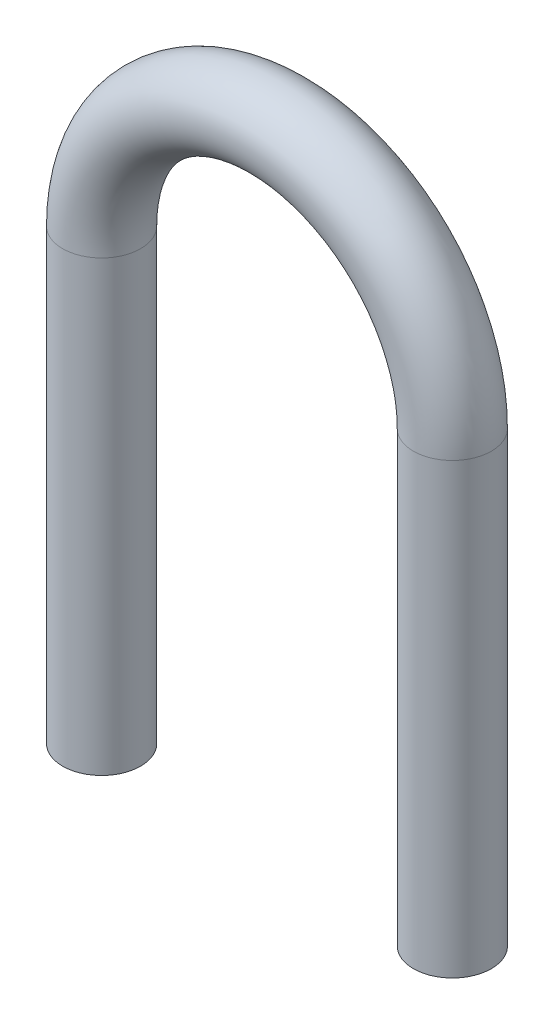
SolidWorks part; units mm, degrees
material "Stainless Steel (ferritic)"
ref_plane "Front Plane" through (0, 0, 0) normal (0, 0, 1) x (1, 0, 0)
ref_plane "Top Plane" through (0, 0, 0) normal (0, 1, 0) x (1, 0, 0)
ref_plane "Right Plane" through (0, 0, 0) normal (1, 0, 0) x (0, 0, -1)
sketch "Sketch1" plane through (0, 0, 0) normal (0, 0, 1) x (1, 0, 0)
  line L0 (-13.5, -13.5) -> (-13.5, -48)
  line L1 (13.5, -13.5) -> (13.5, -48)
  arc A0 (13.5, -13.5) -> (-13.5, -13.5) centre (0, -13.5) ccw
  point P3 (0, 0)
  dimension "D1" = 13.5
  dimension "D2" = 48
ref_plane "Plane1" through (0, -48, 0) normal (0, 1, 0) x (1, 0, 0)
sketch "Sketch2" plane through (0, -48, 0) normal (0, 1, 0) x (1, 0, 0)
  circle A0 centre (-13.5, 0) radius 3
  dimension "D1" = 6
sweep "Sweep1" add profiles "Sketch2" path "Sketch1"
